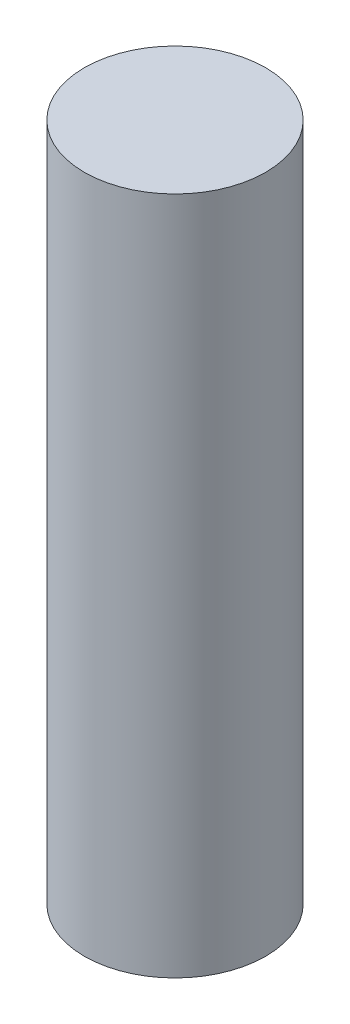
SolidWorks part; units mm, degrees
ref_plane "Front Plane" through (0, 0, 0) normal (0, 0, 1) x (1, 0, 0)
ref_plane "Top Plane" through (0, 0, 0) normal (0, 1, 0) x (1, 0, 0)
ref_plane "Right Plane" through (0, 0, 0) normal (1, 0, 0) x (0, 0, -1)
sketch "Sketch1" plane through (0, 0, 0) normal (0, 1, 0) x (1, 0, 0)
  circle A0 centre (0, 0) radius 13.35
extrude "Boss-Extrude1" add sketch "Sketch1" along normal blind 100
